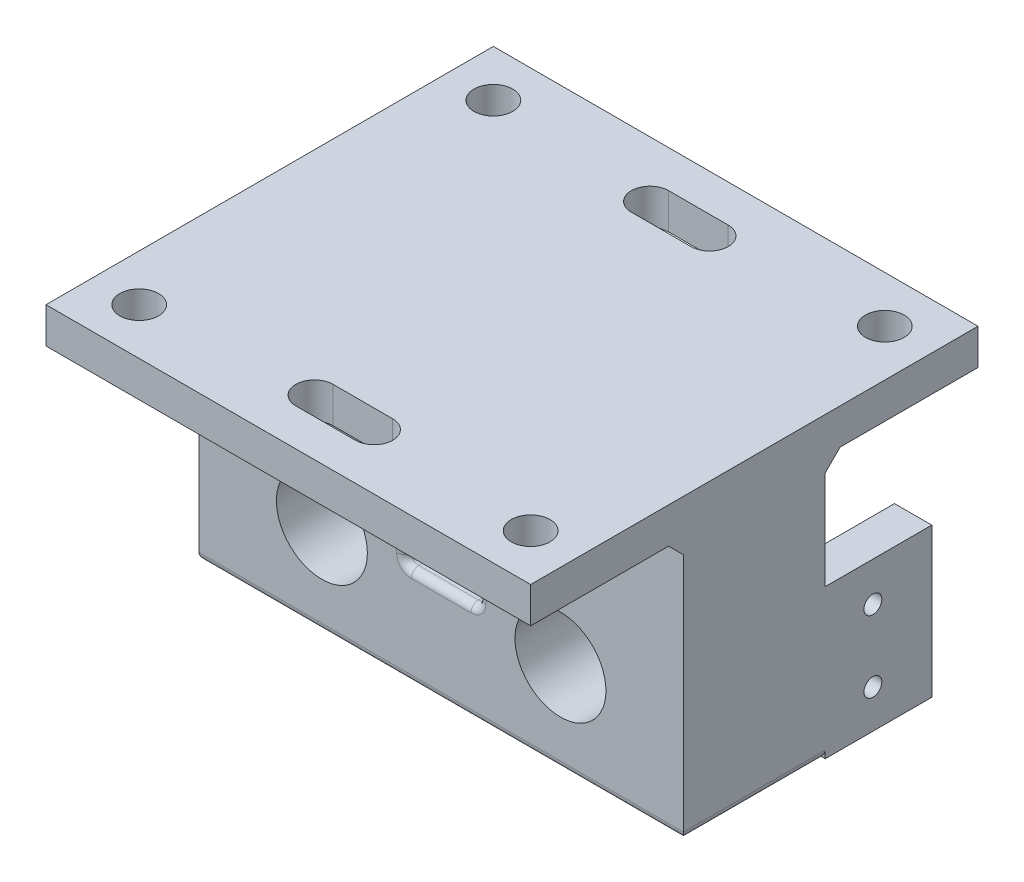
SolidWorks part; units mm, degrees
ref_plane "Front Plane" through (0, 0, 0) normal (0, 0, 1) x (1, 0, 0)
ref_plane "Top Plane" through (0, 0, 0) normal (0, 1, 0) x (1, 0, 0)
ref_plane "Right Plane" through (0, 0, 0) normal (1, 0, 0) x (0, 0, -1)
sketch "Sketch1" plane through (0, 0, 0) normal (0, 0, 1) x (1, 0, 0)
  line L0 (-2, 0) -> (30, 0) construction
  line L1 (-18.5, -12.2) -> (46.5, -12.2)
  line L2 (-18.5, -12.2) -> (-18.5, 27.8)
  line L3 (-18.5, 27.8) -> (46.5, 27.8)
  line L4 (46.5, 27.8) -> (46.5, -12.2)
  circle A0 centre (-2, 0) radius 6.1
  circle A1 centre (30, 0) radius 6.1
  point P7 (14, -12.2)
  point P8 (14, 0)
  dimension "D1" = 12.2
  dimension "D3" = 12.2
  dimension "D5" = 12.2
  dimension "D2" = 32
  dimension "D4" = 40
  dimension "D6" = 65
extrude "Boss-Extrude1" add sketch "Sketch1" against normal blind 19
ref_plane "Plane1" through (0, 0, -9.5) normal (0, 0, 1) x (1, 0, 0)
sketch "Sketch4" plane through (0, 0, -9.5) normal (0, 0, 1) x (1, 0, 0)
  line L0 (-18.5, 27.8) -> (46.5, 27.8)
  line L1 (46.5, 27.8) -> (46.5, 13)
  line L2 (46.5, -12.2) -> (46.5, 27.8) construction
  line L3 (46.5, 13) -> (-18.5, 13)
  line L4 (-18.5, 27.8) -> (-18.5, -12.2) construction
  line L5 (-18.5, 13) -> (-18.5, 27.8)
extrude "Boss-Extrude2" add sketch "Sketch4" along normal mid plane 70
sketch "Sketch6" plane through (0, 0, 0) normal (0, 0, 1) x (1, 0, 0)
  line L0 (14, 13) -> (14, -12.2) construction
  line L1 (-18.5, 13) -> (46.5, 13) construction
  line L2 (-18.5, -12.2) -> (46.5, -12.2) construction
  line L3 (9, 13) -> (19, 13)
  line L4 (9, 13) -> (9, 1)
  line L5 (19, 1) -> (19, 13)
  line L6 (9, 1) -> (19, 1)
  point P8 (14, 13)
  dimension "D1" = 10
  dimension "D2" = 12
extrude "Cut-Extrude1" cut sketch "Sketch6" against normal through all
sketch "Sketch7" plane through (-18.5, 0, 0) normal (-1, 0, 0) x (0, 0, 1)
  line L0 (-44.5, 27.8) -> (-44.5, 13) construction
  line L1 (-9.5, 27.8) -> (-9.5, -12.2) construction
  line L2 (-44.5, 27.8) -> (25.5, 27.8) construction
  line L3 (-19, -12.2) -> (0, -12.2) construction
  line L4 (-44.5, 16.5761) -> (-44.5, 13)
  line L5 (-44.5, 13) -> (-19, 13)
  line L6 (0, 13) -> (25.5, 13)
  line L7 (25.5, 13) -> (25.5, 16.5761)
  line L8 (25.5, 27.8) -> (25.5, 13) construction
  arc A0 (-44.5, 16.5761) -> (-19, 13) centre (-20.5063, 94.9639) ccw
  arc A1 (25.5, 16.5761) -> (0, 13) centre (1.5063, 94.9639) cw
  line M2 (-44.5, 13) -> (-19, 13)
  line M7 (25.5, 13) -> (25.5, 27.8)
  line M9 (-44.5, 27.8) -> (-44.5, 13)
extrude "Cut-Extrude2" [suppressed] cut sketch "Sketch7" against normal through all contours A0 M9 M2 | A1 L6 M7
sketch "Sketch8" plane through (0, 27.8, 0) normal (0, 1, 0) x (1, 0, 0)
  line L0 (-18.3079, 9.5) -> (18.3079, 9.5) construction
  line L2 (46.5, -25.5) -> (-18.5, -25.5) construction
  line L3 (18, 32) -> (10, 32) construction
  line L4 (18, 29.5) -> (10, 29.5)
  line L5 (18, 34.5) -> (10, 34.5)
  line L6 (18, -13) -> (10, -13) construction
  line L7 (18, -10.5) -> (10, -10.5)
  line L8 (18, -15.5) -> (10, -15.5)
  arc A0 (18, 29.5) -> (18, 34.5) centre (18, 32) ccw
  arc A1 (10, 34.5) -> (10, 29.5) centre (10, 32) ccw
  arc A2 (18, -10.5) -> (18, -15.5) centre (18, -13) cw
  arc A3 (10, -15.5) -> (10, -10.5) centre (10, -13) cw
  point P8 (14, 32)
  point P16 (14, -13)
  dimension "D2" = 2.5
  dimension "D3" = 12.5
  dimension "D1" = 8
extrude "Cut-Extrude3" cut sketch "Sketch8" against normal through all
fillet "Fillet1" radius 1 12 edges at (19, 7, -19) (9, 7, -19) (9, 7, 0) (19, 7, 0) (46.5, -12.2, -9.5) (14, -12.2, -19) (-18.5, -12.2, -9.5) (14, -12.2, 0) (14, 1, -19) (14, 1, 0) (9, 1, -9.5) (19, 1, -9.5)
sketch "Sketch9" plane through (0, 0, 25.5) normal (0, 0, 1) x (1, 0, 0)
  line L4 (-18.5, 27.8) -> (-18.5, 13)
  line L5 (-18.5, 13) -> (46.5, 13)
  line L6 (46.5, 13) -> (46.5, 27.8)
  line L7 (46.5, 27.8) -> (-18.5, 27.8)
  line L8 (-18.5, 27.8) -> (-18.5, 13)
  line L9 (-18.5, 13) -> (46.5, 13)
  line L10 (46.5, 13) -> (46.5, 27.8)
  line L11 (46.5, 27.8) -> (-18.5, 27.8)
  dimension "D1" = 0
extrude "Cut-Extrude4" cut sketch "Sketch9" against normal blind 5
sketch "Sketch10" plane through (0, 0, -44.5) normal (0, 0, -1) x (-1, 0, 0)
  line L4 (18.5, 13) -> (18.5, 27.8)
  line L5 (18.5, 27.8) -> (-46.5, 27.8)
  line L6 (-46.5, 27.8) -> (-46.5, 13)
  line L7 (-46.5, 13) -> (18.5, 13)
  line L8 (18.5, 13) -> (18.5, 27.8)
  line L9 (18.5, 27.8) -> (-46.5, 27.8)
  line L10 (-46.5, 27.8) -> (-46.5, 13)
  line L11 (-46.5, 13) -> (18.5, 13)
  dimension "D1" = 0
extrude "Cut-Extrude5" cut sketch "Sketch10" against normal blind 5
sketch "Sketch11" plane through (0, 27.8, 0) normal (0, 1, 0) x (1, 0, 0)
  line L0 (46.5, -20.5) -> (40.25, -20.5) construction
  line L1 (46.5, -20.5) -> (-18.5, -20.5) construction
  line L2 (40.25, -20.5) -> (40.25, -14.25) construction
  line L3 (-18.5, 9.5) -> (46.5, 9.5) construction
  line L4 (-18.5, 39.5) -> (-18.5, -20.5) construction
  line L5 (46.5, 39.5) -> (46.5, -20.5) construction
  line L6 (14, -20.5) -> (14, 39.5) construction
  line L7 (-18.5, 39.5) -> (46.5, 39.5) construction
  circle A0 centre (40.25, -14.25) radius 2.6
  circle A1 centre (40.25, 33.25) radius 2.6
  circle A2 centre (-12.25, 33.25) radius 2.6
  circle A3 centre (-12.25, -14.25) radius 2.6
  dimension "D1" = 5.2
extrude "Cut-Extrude6" cut sketch "Sketch11" against normal through all
sketch "Sketch12" plane through (0, 13, 0) normal (0, -1, 0) x (1, 0, 0)
  line L12 (-18.5, -39.5) -> (46.5, -39.5)
  line L13 (46.5, -39.5) -> (46.5, -19)
  line L14 (46.5, -19) -> (20, -19)
  line L15 (19, -18) -> (19, -1)
  line L16 (20, 0) -> (46.5, 0)
  line L17 (46.5, 0) -> (46.5, 20.5)
  line L18 (46.5, 20.5) -> (-18.5, 20.5)
  line L19 (-18.5, 20.5) -> (-18.5, 0)
  line L20 (-18.5, 0) -> (8, 0)
  line L21 (9, -1) -> (9, -18)
  line L22 (8, -19) -> (-18.5, -19)
  line L23 (-18.5, -19) -> (-18.5, -39.5)
  line L24 (-18.5, -39.5) -> (46.5, -39.5)
  line L25 (46.5, -39.5) -> (46.5, -19)
  line L26 (46.5, -19) -> (20, -19)
  line L27 (19, -18) -> (19, -1)
  line L28 (20, 0) -> (46.5, 0)
  line L29 (46.5, 0) -> (46.5, 20.5)
  line L30 (46.5, 20.5) -> (-18.5, 20.5)
  line L31 (-18.5, 20.5) -> (-18.5, 0)
  line L32 (-18.5, 0) -> (8, 0)
  line L33 (9, -1) -> (9, -18)
  line L34 (8, -19) -> (-18.5, -19)
  line L35 (-18.5, -19) -> (-18.5, -39.5)
  arc A4 (19, -18) -> (20, -19) centre (20, -18) ccw
  arc A5 (20, 0) -> (19, -1) centre (20, -1) ccw
  arc A6 (9, -1) -> (8, 0) centre (8, -1) ccw
  arc A7 (8, -19) -> (9, -18) centre (8, -18) ccw
  arc A8 (19, -18) -> (20, -19) centre (20, -18) ccw
  arc A9 (20, 0) -> (19, -1) centre (20, -1) ccw
  arc A10 (9, -1) -> (8, 0) centre (8, -1) ccw
  arc A11 (8, -19) -> (9, -18) centre (8, -18) ccw
  dimension "D1" = 0
extrude "Cut-Extrude7" cut sketch "Sketch12" against normal blind 10
chamfer "Chamfer1" distance 2 angle 45 10 edges at (33.25, 23, 0) (19.2929, 23, -0.2929) (19, 23, -9.5) (19.2929, 23, -18.7071) (33.25, 23, -19) (-5.25, 23, 0) (8.7071, 23, -0.2929) (9, 23, -9.5) (8.7071, 23, -18.7071) (-5.25, 23, -19)
sketch "Sketch13" plane through (46.5, 0, 0) normal (1, 0, 0) x (0, 0, -1)
  line L0 (19, 7.8) -> (33.3, 7.8)
  line L1 (19, -11.2) -> (19, 21) construction
  line L2 (33.3, 7.8) -> (33.3, -12.2)
  line L3 (33.3, -12.2) -> (19, -12.2)
  line L4 (19, -12.2) -> (19, 7.8)
  circle A0 centre (25.4, 2.55) radius 1.2
  circle A1 centre (25.4, -7.05) radius 1.2
extrude "Boss-Extrude3" add sketch "Sketch13" against normal blind 5
